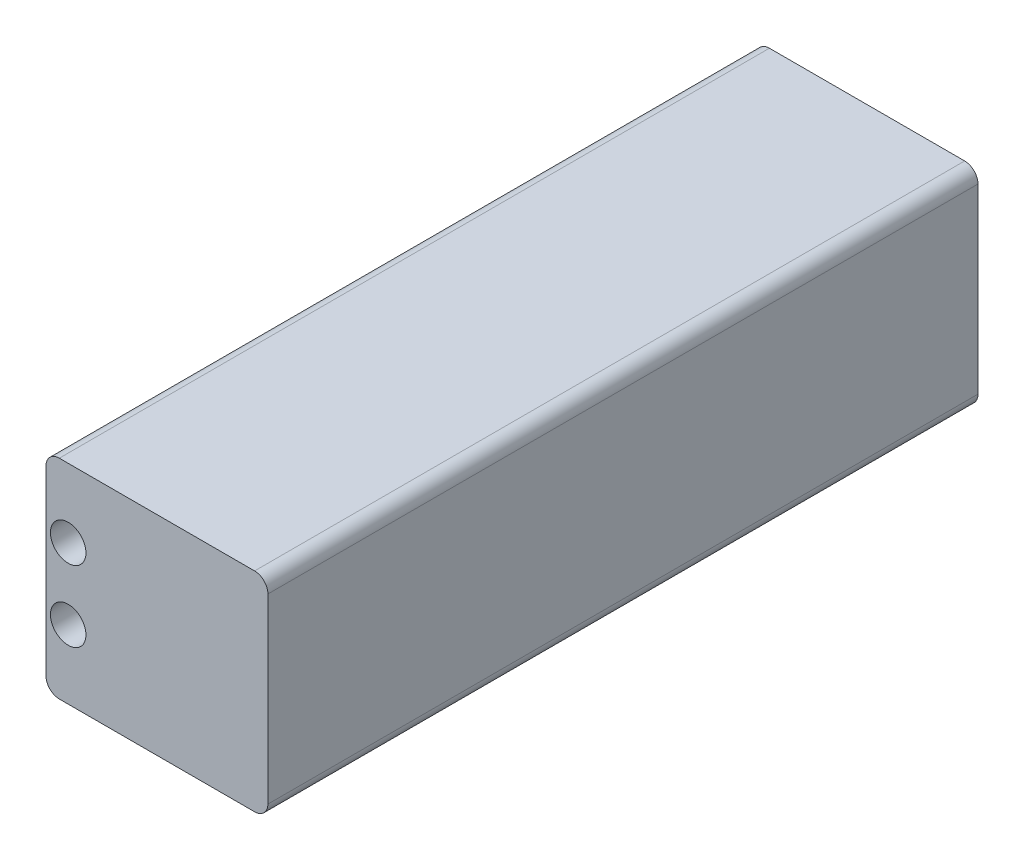
SolidWorks part; units mm, degrees
ref_plane "Front Plane" through (0, 0, 0) normal (0, 0, 1) x (1, 0, 0)
ref_plane "Top Plane" through (0, 0, 0) normal (0, 1, 0) x (1, 0, 0)
ref_plane "Right Plane" through (0, 0, 0) normal (1, 0, 0) x (0, 0, -1)
sketch "Sketch1" plane through (0, 0, 0) normal (0, 1, 0) x (1, 0, 0)
  line L1 (-25, -80) -> (25, -80)
  line L2 (-25, -80) -> (-25, 80)
  line L3 (-25, 80) -> (25, 80)
  line L4 (25, -80) -> (25, 80)
  line L5 (-25, -80) -> (25, 80) construction
  line L6 (-25, 80) -> (25, -80) construction
  point P0 (0, 0)
  dimension "D1" = 160
  dimension "D2" = 50
extrude "Boss-Extrude1" add sketch "Sketch1" along normal blind 47
sketch "Sketch2" plane through (0, 0, 80) normal (0, 0, 1) x (1, 0, 0)
  line L0 (-25, 47) -> (-25, 0) construction
  line L1 (-25, 23.5) -> (0, 23.5) construction
  circle A0 centre (-20, 31.5) radius 4
  circle A1 centre (-20, 15.5) radius 4
  point P4 (-25, 23.5)
  dimension "D1" = 8
  dimension "D2" = 5
  dimension "D3" = 8
extrude "Cut-Extrude1" cut sketch "Sketch2" against normal blind 10
fillet "Fillet1" radius 3 4 edges at (-25, 0, 0) (25, 0, 0) (-25, 47, 0) (25, 47, 0)
